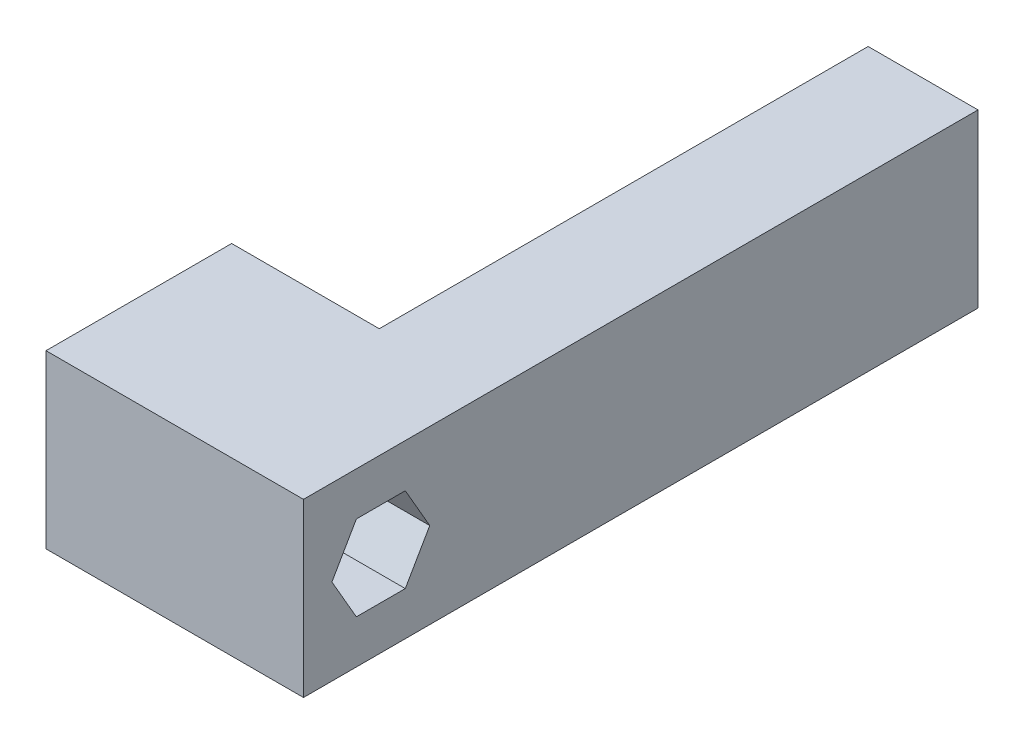
SolidWorks part; units mm, degrees
ref_plane "Front Plane" through (0, 0, 0) normal (0, 0, 1) x (1, 0, 0)
ref_plane "Top Plane" through (0, 0, 0) normal (0, 1, 0) x (1, 0, 0)
ref_plane "Right Plane" through (0, 0, 0) normal (1, 0, 0) x (0, 0, -1)
sketch "Sketch1" plane through (0, 0, 0) normal (1, 0, 0) x (0, 0, -1)
  line L0 (0, -12.7) -> (12.446, -12.7)
  line L1 (0, 0) -> (75.4115, 0)
  line L2 (0, 0) -> (0, -25.4)
  line L3 (0, -25.4) -> (75.4115, -25.4)
  line L4 (75.4115, 0) -> (75.4115, -25.4)
  line L12 (19.685, -12.7) -> (16.0655, -6.4308)
  line L19 (16.0655, -6.4308) -> (8.8265, -6.4308)
  line L20 (8.8265, -6.4308) -> (5.207, -12.7)
  line L21 (5.207, -12.7) -> (8.8265, -18.9692)
  line L22 (8.8265, -18.9692) -> (16.0655, -18.9692)
  line L23 (16.0655, -18.9692) -> (19.685, -12.7)
  circle A0 centre (12.446, -12.7) radius 6.2692 construction
  dimension "D1" = 12.446
  dimension "D2" = 14.478
  dimension "D4" = 25.4
extrude "Boss-Extrude1" add sketch "Sketch1" along normal blind 12.7
sketch "Sketch2" plane through (0, 0, 0) normal (-1, 0, 0) x (0, 0, 1)
  line L0 (-12.446, -6.4308) -> (-12.446, -12.7)
  line L1 (-16.0655, -6.4308) -> (-8.8265, -6.4308) construction
  line L2 (-75.4115, 0) -> (-75.4115, -25.4) construction
  circle A0 centre (-12.446, -12.7) radius 7.239
sketch "Sketch3" plane through (0, 0, -75.4115) normal (0, 0, -1) x (-1, 0, 0)
  line L1 (0, 0) -> (-12.7, 0)
  line L2 (0, 0) -> (0, -25.4)
  line L3 (0, -25.4) -> (-12.7, -25.4)
  line L4 (-12.7, 0) -> (-12.7, -25.4)
extrude "Boss-Extrude2" add sketch "Sketch3" along normal blind 25.4
sketch "Sketch4" plane through (0, 0, 0) normal (-1, 0, 0) x (0, 0, 1)
  line L0 (0, 0) -> (-100.8115, 0) construction
  line L1 (-28.4713, 0) -> (-20.8283, 0)
  line L2 (-28.4713, 0) -> (-28.4713, -25.4)
  line L3 (-28.4713, -25.4) -> (-20.8283, -25.4)
  line L4 (-20.8283, 0) -> (-20.8283, -25.4)
  line L5 (0, -25.4) -> (-100.8115, -25.4) construction
extrude "Boss-Extrude4" add sketch "Sketch4" along normal blind 25.4
sketch "Sketch5" plane through (0, 0, 0) normal (-1, 0, 0) x (0, 0, 1)
  line L1 (-100.8115, 0) -> (-28.4713, 0)
  line L2 (-100.8115, 0) -> (-100.8115, -25.4)
  line L3 (-100.8115, -25.4) -> (-28.4713, -25.4)
  line L4 (-28.4713, 0) -> (-28.4713, -25.4)
extrude "Cut-Extrude1" cut sketch "Sketch5" against normal blind 6.604
sketch "Sketch6" plane through (0, 0, 0) normal (-1, 0, 0) x (0, 0, 1)
  line L0 (-20.8283, 0) -> (0, 0)
  line L1 (0, 0) -> (0, -25.4)
  line L2 (0, -25.4) -> (-20.8283, -25.4)
  line L3 (-20.8283, -25.4) -> (-20.8283, 0)
  line L5 (-8.8265, -6.4308) -> (-16.0655, -6.4308)
  line L6 (-16.0655, -6.4308) -> (-19.685, -12.7)
  line L7 (-19.685, -12.7) -> (-16.0655, -18.9692)
  line L8 (-16.0655, -18.9692) -> (-8.8265, -18.9692)
  line L9 (-8.8265, -18.9692) -> (-5.207, -12.7)
  line L10 (-5.207, -12.7) -> (-8.8265, -6.4308)
  circle A0 centre (-12.446, -12.7) radius 6.2692 construction
extrude "Boss-Extrude5" add sketch "Sketch6" along normal up to surface (25.4 mm away) up to face at (-25.4, -12.7, -24.6498)
sketch "Sketch7" plane through (6.604, 0, 0) normal (-1, 0, 0) x (0, 0, 1)
  line L1 (-100.8115, 0) -> (-28.4713, 0)
  line L2 (-100.8115, 0) -> (-100.8115, -25.4)
  line L3 (-100.8115, -25.4) -> (-28.4713, -25.4)
  line L4 (-28.4713, 0) -> (-28.4713, -25.4)
extrude "Boss-Extrude6" add sketch "Sketch7" along normal blind 10.16
sketch "Sketch8" plane through (0, 0, 0) normal (0, 0, 1) x (1, 0, 0)
  line L1 (12.7, 0) -> (-25.4, 0)
  line L2 (12.7, 0) -> (12.7, -25.4)
  line L3 (12.7, -25.4) -> (-25.4, -25.4)
  line L4 (-25.4, 0) -> (-25.4, -25.4)
extrude "Cut-Extrude2" cut sketch "Sketch8" against normal blind 1
